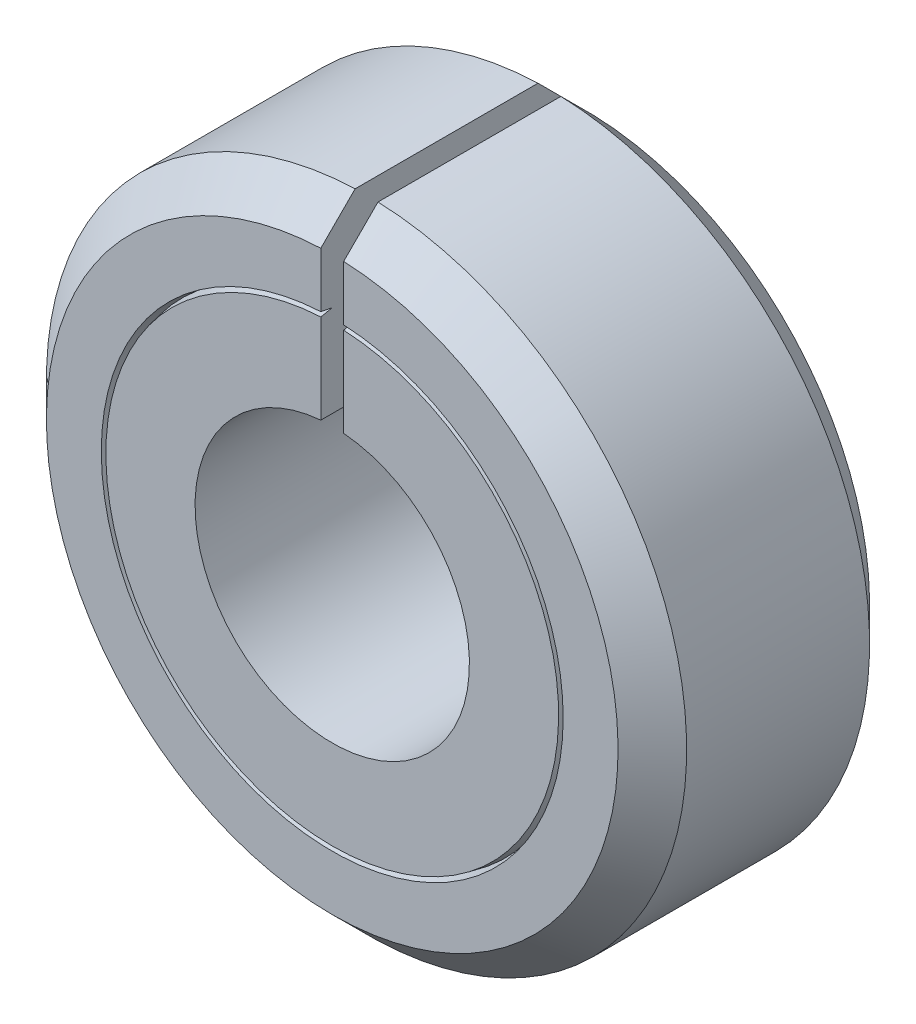
SolidWorks part; units mm, degrees
ref_plane "Front Plane" through (0, 0, 0) normal (0, 0, 1) x (1, 0, 0)
ref_plane "Top Plane" through (0, 0, 0) normal (0, 1, 0) x (1, 0, 0)
ref_plane "Right Plane" through (0, 0, 0) normal (1, 0, 0) x (0, 0, -1)
sketch "Sketch1" plane through (0, 0, 0) normal (1, 0, 0) x (0, 0, -1)
  line L0 (-10.1123, 0) -> (9.9442, 0) construction
  line L1 (-5.5, 6) -> (5.5, 6)
  line L2 (-5.5, 6) -> (-5.5, 9.9)
  line L3 (-4, 14) -> (4, 14)
  line L4 (5.5, 6) -> (5.5, 9.9)
  line L5 (-5.5, 6) -> (5.5, 14) construction
  line L6 (-5.5, 14) -> (5.5, 6) construction
  line L7 (-5.5, 12.5) -> (-4, 14)
  line L8 (4, 14) -> (5.5, 12.5)
  line L15 (-5.5, 10) -> (5, 10) construction
  line L16 (5.5, 10.1) -> (5, 10)
  line L17 (5, 10) -> (5.5, 9.9)
  line L18 (-5.5, 10.1) -> (-5, 10)
  line L19 (-5, 10) -> (-5.5, 9.9)
  line L20 (-5.5, 10.1) -> (-5.5, 12.5)
  line L21 (5.5, 10.1) -> (5.5, 12.5)
  point P0 (0, 10)
  point P12 (0, 10)
  point P23 (5.5383, 9.7358)
  dimension "D1" = 8
  dimension "D2" = 11
  dimension "D3" = 10
  dimension "D4" = 0.1
  dimension "D5" = 0.1
  dimension "D6" = 0.1
  dimension "D7" = 0.1
  dimension "D10" = 0.5
  dimension "D11" = 0.5
revolve "Revolve1" add sketch "Sketch1" angle 360 about L0
sketch "Sketch3" plane through (0, 0, 0) normal (0, 0, 1) x (1, 0, 0)
  line L1 (-0.5, 14) -> (0.5, 14)
  line L2 (-0.5, 14) -> (-0.5, 0)
  line L3 (-0.5, 0) -> (0.5, 0)
  line L4 (0.5, 14) -> (0.5, 0)
  line L5 (-0.5, 14) -> (0.5, 0) construction
  line L6 (-0.5, 0) -> (0.5, 14) construction
  point P0 (0, 7)
  point P5 (0, 0)
  dimension "D1" = 1
  dimension "D2" = 14
extrude "Cut-Extrude2" cut sketch "Sketch3" against normal mid plane 30
